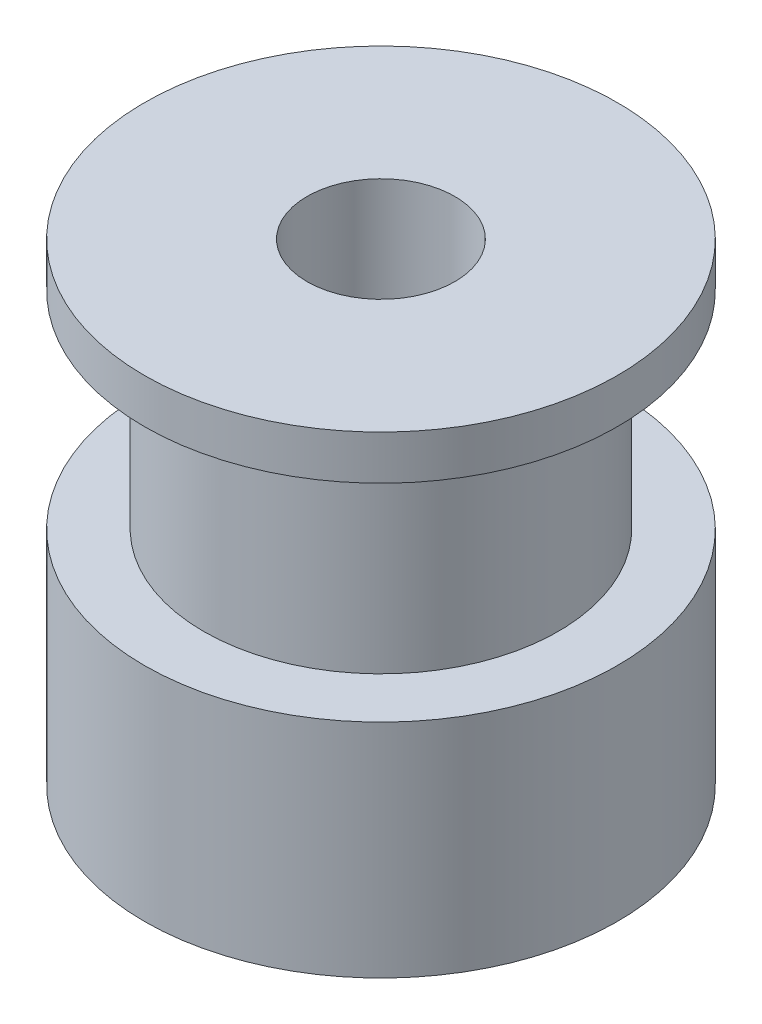
SolidWorks part; units mm, degrees
ref_plane "Plano frontal" through (0, 0, 0) normal (0, 0, 1) x (1, 0, 0)
ref_plane "Plano superior" through (0, 0, 0) normal (0, 1, 0) x (1, 0, 0)
ref_plane "Plano direito" through (0, 0, 0) normal (1, 0, 0) x (0, 0, -1)
sketch "Esboço1" plane through (0, 0, 0) normal (0, 0, 1) x (1, 0, 0)
  line L0 (0, 15.0124) -> (0, -4.167) construction
  line L1 (2.5, 16) -> (8, 16)
  line L2 (8, 16) -> (8, 14.5)
  line L3 (8, 14.5) -> (6, 14.5)
  line L4 (6, 14.5) -> (6, 7.5)
  line L5 (6, 7.5) -> (8, 7.5)
  line L6 (8, 7.5) -> (8, 0)
  line L7 (8, 0) -> (2.5, 0)
  line L8 (2.5, 16) -> (2.5, 0)
  point P3 (5.25, 0)
  point P11 (0, 15.0124)
  point P13 (0, -4.167)
  dimension "D1" = 5
  dimension "D2" = 16
  dimension "D3" = 16
  dimension "D4" = 7.5
  dimension "D5" = 7
  dimension "D6" = 12
revolve "Revolução1" add sketch "Esboço1" angle 360 about L0
